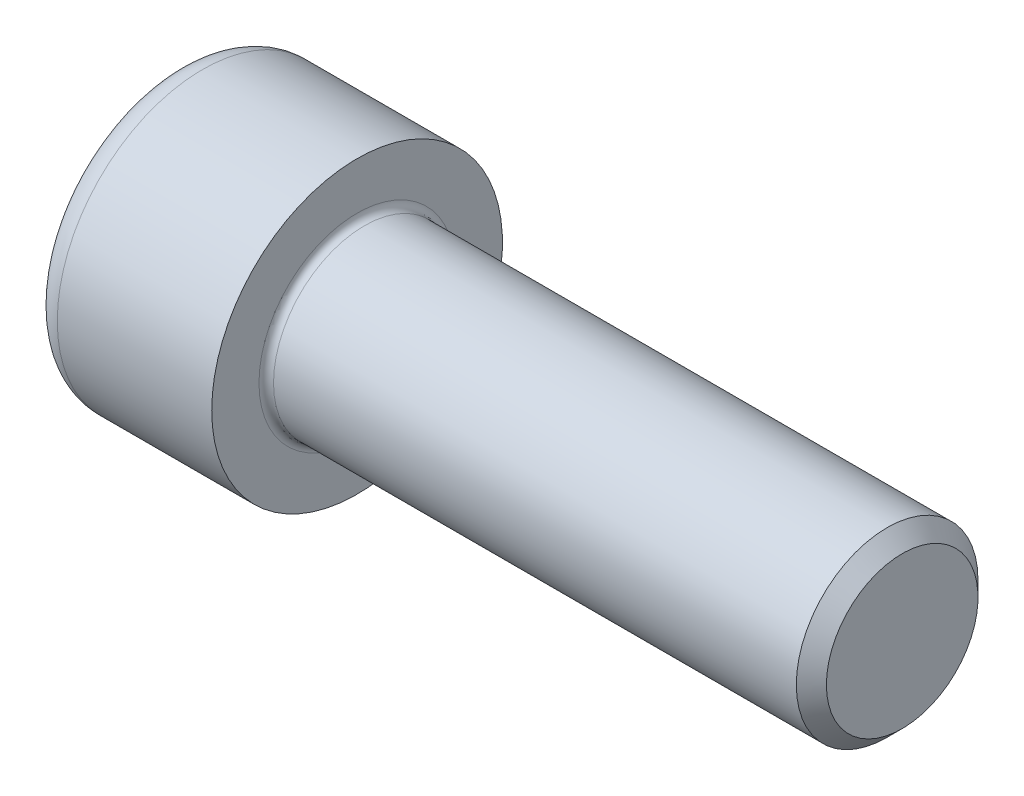
SolidWorks part; units mm, degrees
ref_plane "Plane1" through (0, 0, 0) normal (0, 0, 1) x (1, 0, 0)
ref_plane "Plane2" through (0, 0, 0) normal (0, 1, 0) x (1, 0, 0)
ref_plane "Plane3" through (0, 0, 0) normal (1, 0, 0) x (0, 0, -1)
sketch "BodySke" plane through (0, 0, 0) normal (0, 0, 1) x (1, 0, 0)
  line L0 (0, 0) -> (0, 8)
  line L1 (0, 8) -> (10, 8)
  line L2 (10, 8) -> (10, 5)
  line L3 (10, 5) -> (39.172, 5)
  line L4 (40, 4.172) -> (40, 0)
  line L5 (40, 0) -> (0, 0)
  line L6 (-31.75, 0) -> (127, 0) construction
  line L8 (40, 4.172) -> (39.172, 5)
  line L10 (40, -4.172) -> (39.172, -5) construction
  line L11 (11.5, 9.525) -> (11.5, 3.175) construction
  line L12 (10, 9.525) -> (10, 3.175) construction
  line L13 (-20, 9.525) -> (-20, 3.175) construction
  dimension "Diameter" = 10
  dimension "Head_ht" = 10
  dimension "Length" = 30
  dimension "Body_ch_ang" = 45
  dimension "Head_dia" = 16
  dimension "Minor_dia" = 8.344
  dimension "Advance" = 1.5
  dimension "Thread_nom" = 30
  dimension "Thread_length" = 60
revolve "Base-Revolve" add sketch "BodySke"
cosmetic thread "ThreadCosmetic"
fillet "Fillet1" radius 0.4 1 edges at (10, 0, 5)
fillet "Fillet2" radius 1.5 1 edges at (0, 0, 8)
sketch "Sketch2" plane through (0, 0, 0) normal (0, 0, 1) x (1, 0, 0)
  line L0 (0, 4.0575) -> (5, 4.0575)
  line L1 (5, 4.0575) -> (7.3426, 0)
  line L2 (-31.75, 0) -> (127, 0) construction
  line L3 (7.3426, 0) -> (0, 0)
  line L4 (0, 0) -> (0, 4.0575)
  line L6 (0, 0) -> (47.625, 0) construction
  dimension "D1" = 4.0575
  dimension "D2" = 60
  dimension "Depth" = 5
revolve "Hex-PreBroach" cut sketch "Sketch2" angle 360 about L6
sketch "Sketch3" plane through (0, 0, 0) normal (-1, 0, 0) x (0, 0.5, 0.866)
  line L0 (2.3426, 4.0575) -> (-2.3426, 4.0575)
  line L1 (-2.3426, 4.0575) -> (-4.6852, 0)
  line L2 (2.3426, 4.0575) -> (4.6852, 0)
  line L3 (2.3426, -4.0575) -> (4.6852, 0)
  line L4 (2.3426, -4.0575) -> (-2.3426, -4.0575)
  line L5 (-2.3426, -4.0575) -> (-4.6852, 0)
  dimension "D1" = 4.0575
  dimension "D2" = 4.0575
  dimension "Hex_size" = 8.115
extrude "Hex" cut sketch "Sketch3" against normal blind 5
sketch "ThdSchSke" plane through (0, 0, 0) normal (0, 0, 1) x (1, 0, 0)
  line L0 (14.5, -4.172) -> (13.9202, -5)
  line L1 (14.5, -4.172) -> (15.0798, -5)
  line L2 (15.0798, -5) -> (15.0798, -6.25)
  line L3 (-3.175, 0) -> (5.1513, 0) construction
  line L4 (0, 6.5) -> (0, -6.5) construction
  line L5 (15.0798, -6.25) -> (13.9202, -6.25)
  line L6 (13.9202, -6.25) -> (13.9202, -5)
  dimension "Thread_minor" = 8.344
  dimension "Diameter" = 10
  dimension "Start" = 14.5
  dimension "SideAngle" = 55
  dimension "VeeAngle" = 70
  dimension "Overcut" = 12.5
revolve "ThreadSchematic" [suppressed] cut sketch "ThdSchSke" angle 360 about L3
pattern_linear "ThdSchPat" [suppressed]
equation "\"D2@Sketch3\" = \"Hex_size@Sketch3\" / 2"
equation "\"D1@Sketch3\" = \"Hex_size@Sketch3\" / 2"
equation "\"D1@Sketch2\" = \"Hex_size@Sketch3\" / 2"
equation "\"Thread_minor@ThreadCosmetic\"  =  \"Minor_dia@BodySke\""
equation "\"Depth@Sketch2\" =  \"Key_eng@Hex\""
equation "\"Thread_length@ThreadCosmetic\" = ((sgn( (\"Length@BodySke\" - \"Advance@BodySke\" * 3.0) - \"Thread_nom@BodySke\" )-1)*( (\"Length@BodySke\" - \"Advance@BodySke\" * 3.0) - \"Thread_nom@BodySke\" ))/-2+ \"Thread_nom@BodySke\""
equation "\"Thread_minor@ThdSchSke\" = \"Minor_dia@BodySke\""
equation "\"Diameter@ThdSchSke\" = \"Diameter@BodySke\""
equation "\"Overcut@ThdSchSke\" = \"Diameter@BodySke\" * 1.25"
equation "\"Start@ThdSchSke\" = \"Head_ht@BodySke\" + \"Length@BodySke\" - \"Thread_length@ThreadCosmetic\"  '---Non-countersunk---"
equation "\"Num_threads@ThdSchPat\" = int( \"Thread_length@ThreadCosmetic\" / \"Advance@BodySke\" + 0.999 )  + 1"
equation "\"Advance@ThdSchPat\" = \"Thread_length@ThreadCosmetic\" /  (\"Num_threads@ThdSchPat\" - 1) 'relax it"
equation "\"Num_threads@ThdSchPat\" = \"Num_threads@ThdSchPat\" - sgn( \"Num_threads@ThdSchPat\" - 1) '---chamfered tips only---"
